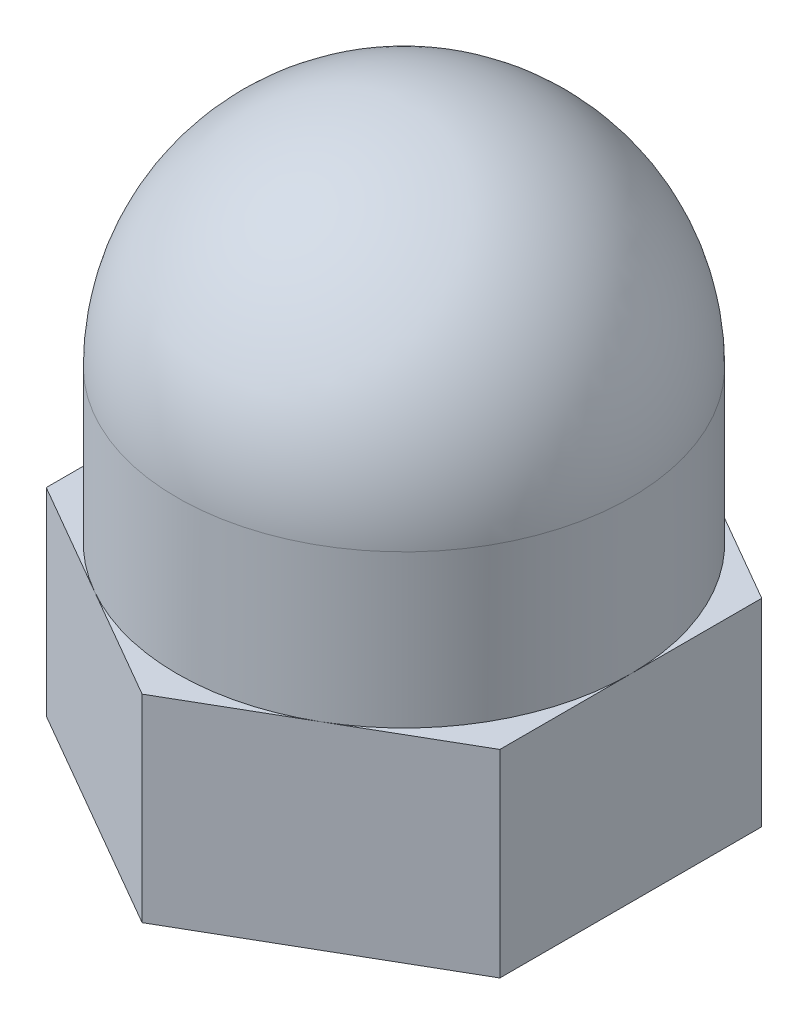
SolidWorks part; units mm, degrees
ref_plane "Płaszczyzna przednia" through (0, 0, 0) normal (0, 0, 1) x (1, 0, 0)
ref_plane "Płaszczyzna górna" through (0, 0, 0) normal (0, 1, 0) x (1, 0, 0)
ref_plane "Płaszczyzna prawa" through (0, 0, 0) normal (1, 0, 0) x (0, 0, -1)
sketch "Szkic1" plane through (0, 0, 0) normal (0, 1, 0) x (1, 0, 0)
  line L1 (0, 3.1754) -> (-2.75, 1.5877)
  line L2 (-2.75, 1.5877) -> (-2.75, -1.5877)
  line L3 (-2.75, -1.5877) -> (0, -3.1754)
  line L4 (0, -3.1754) -> (2.75, -1.5877)
  line L5 (2.75, -1.5877) -> (2.75, 1.5877)
  line L6 (2.75, 1.5877) -> (0, 3.1754)
  circle A0 centre (0, 0) radius 2.75 construction
  circle A1 centre (0, 0) radius 1.5
  dimension "D1" = 3
  dimension "D2" = 5.5
extrude "Dodanie-wyciągnięcie1" add sketch "Szkic1" along normal blind 2.4
sketch "Szkic3" plane through (0, 0, 0) normal (0, 0, 1) x (1, 0, 0)
  line L0 (0, 2.4) -> (0, 7.742) construction
  line L1 (-2.75, 2.4) -> (-2.75, 4.25)
  line L2 (-2.75, 2.4) -> (0, 2.4) construction
  line L3 (2.75, 2.4) -> (2.75, 4.25)
  line L4 (0, 2.4) -> (2.75, 2.4) construction
  line L6 (0, 7) -> (-2.75, 7) construction
  line L7 (-2.75, 0) -> (0, 0) construction
  line L8 (-2.75, 2.4) -> (2.75, 2.4)
  line L9 (0, 7) -> (0, 2.4)
  arc A0 (-2.75, 4.25) -> (2.75, 4.25) centre (0, 4.25) cw
  dimension "D2" = 7
  dimension "D1" = 5.5
revolve "Obrót2" add sketch "Szkic3" angle 360 about L9
